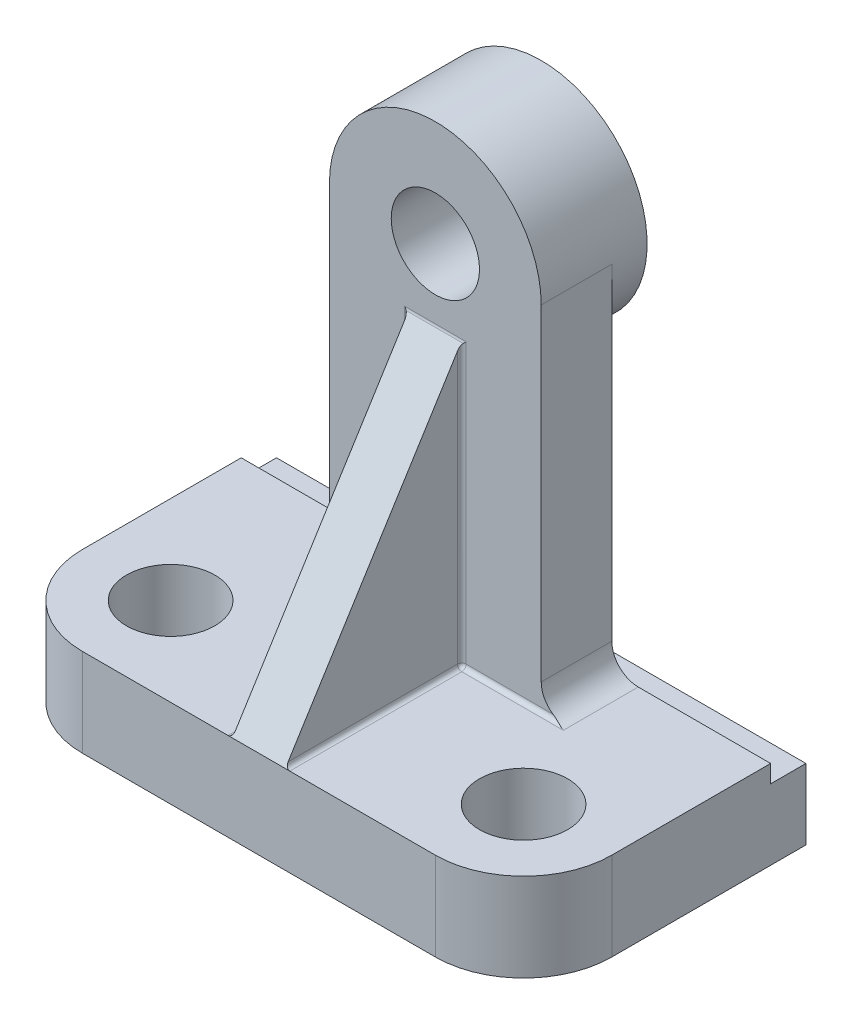
SolidWorks part; units mm, degrees
ref_plane "Front Plane" through (0, 0, 0) normal (0, 0, 1) x (1, 0, 0)
ref_plane "Top Plane" through (0, 0, 0) normal (0, 1, 0) x (1, 0, 0)
ref_plane "Right Plane" through (0, 0, 0) normal (1, 0, 0) x (0, 0, -1)
sketch "Sketch2" plane through (0, 0, 0) normal (0, 1, 0) x (1, 0, 0)
  line L0 (-64.7082, 0) -> (15.2918, 0)
  line L1 (35.2918, 20) -> (35.2918, 64)
  line L4 (35.2918, 20) -> (-131.6865, 20) construction
  line L5 (-84.7082, 20) -> (-84.7082, 64)
  line L6 (-84.7082, 64) -> (35.2918, 64)
  arc A0 (15.2918, 0) -> (35.2918, 20) centre (15.2918, 20) ccw
  arc A2 (-64.7082, 0) -> (-84.7082, 20) centre (-64.7082, 20) cw
  circle A3 centre (-64.7082, 20) radius 10
  circle A4 centre (15.2918, 20) radius 10
  dimension "D1" = 40
  dimension "D2" = 40
  dimension "D5" = 20
  dimension "D6" = 20
  dimension "D3" = 80
  dimension "D4" = 64
extrude "Boss-Extrude1" add sketch "Sketch2" along normal blind 20
sketch "Sketch3" plane through (0, 20, 0) normal (0, 1, 0) x (1, 0, 0)
  line L0 (35.2918, 20) -> (35.2918, 64) construction
  line L1 (-84.7082, 64) -> (35.2918, 64)
  line L2 (-84.7082, 64) -> (-84.7082, 56)
  line L3 (-84.7082, 56) -> (35.2918, 56)
  line L4 (35.2918, 64) -> (35.2918, 56)
  dimension "D1" = 8
extrude "Cut-Extrude1" cut sketch "Sketch3" against normal blind 4
ref_plane "Plane2" through (0, 0, -56) normal (0, 0, -1) x (-1, 0, 0)
sketch "Sketch7" plane through (0, 0, -56) normal (0, 0, -1) x (-1, 0, 0)
  line L0 (24.7082, 20) -> (24.7082, 100) construction
  line L1 (84.7082, 20) -> (-35.2918, 20) construction
  line L7 (24.7082, 20) -> (54.7082, 20)
  line L8 (48.7082, 26) -> (48.7082, 100)
  line L9 (0.7082, 100) -> (0.7082, 26)
  line L10 (-5.2918, 20) -> (24.7082, 20)
  line L11 (-35.2918, 0) -> (84.7082, 0) construction
  circle A1 centre (24.7082, 100) radius 10
  arc A2 (54.7082, 20) -> (48.7082, 26) centre (54.7082, 26) cw
  arc A3 (48.7082, 100) -> (0.7082, 100) centre (24.7082, 100) ccw
  arc A4 (0.7082, 26) -> (-5.2918, 20) centre (-5.2918, 26) cw
  dimension "D1" = 48
  dimension "D3" = 20
  dimension "D4" = 12
  dimension "D5" = 12
  dimension "D2" = 100
extrude "Boss-Extrude2" add sketch "Sketch7" against normal blind 16
sketch "Sketch8" plane through (0, 0, -56) normal (0, 0, -1) x (-1, 0, 0)
  circle A0 centre (24.7082, 100) radius 24
  circle A1 centre (24.7082, 100) radius 10
  dimension "D1" = 48
extrude "Boss-Extrude3" add sketch "Sketch8" along normal blind 8
ref_plane "Plane3" through (-24.7082, 0, 0) normal (-1, 0, 0) x (0, 0, 1)
sketch "Sketch9" plane through (-24.7082, 0, 0) normal (-1, 0, 0) x (0, 0, 1)
  line L1 (-40, 26) -> (-40, 100) construction
  line L3 (0, 20) -> (-20, 20) construction
  line L4 (0, 20) -> (-40, 84)
  line L6 (-56, 20) -> (-20, 20) construction
  dimension "D1" = 64
  dimension "D2" = 40
rib "Rib4" sketch "Sketch9" sketch "Sketch9" thickness 12 extrusion direction parallel to sketch draft on no parameters "D1"=12
fillet "Fillet2" radius 1 7 edges at (-42.7082, 20, -40) (-6.7082, 20, -40) (-30.7082, 20, -20) (-18.7082, 20, -20) (-18.7082, 52, -40) (-30.7082, 52, -40) (-24.7082, 84, -40)
